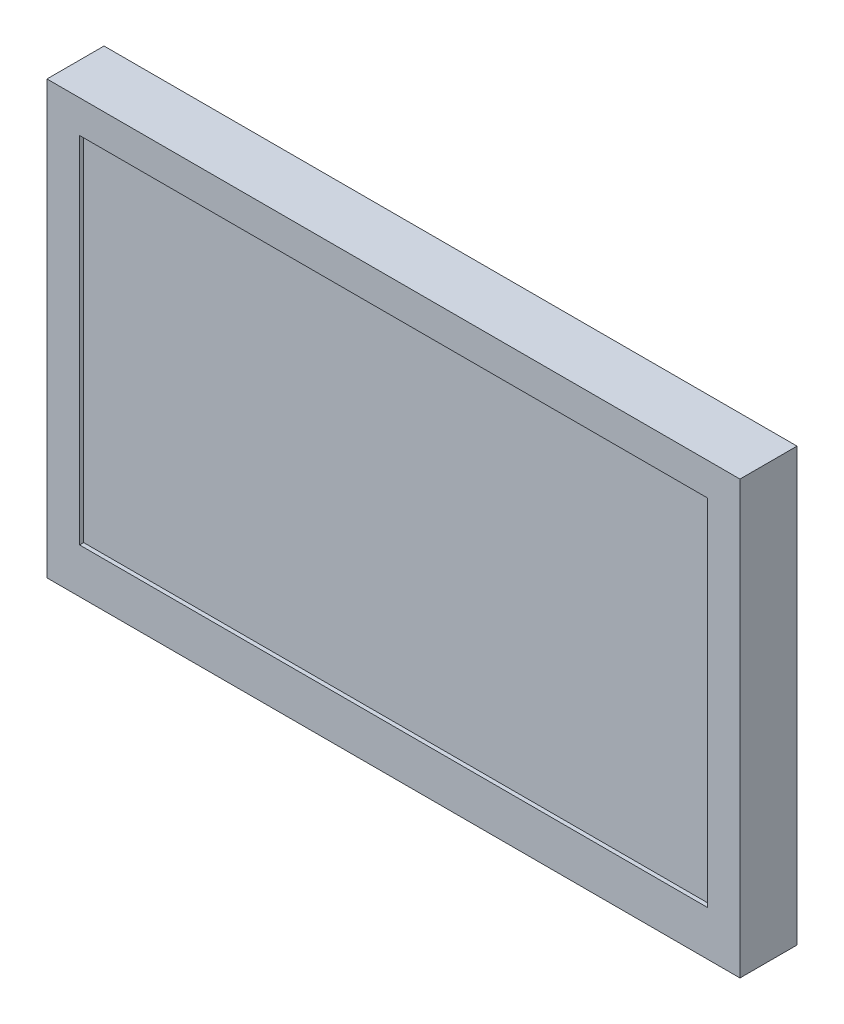
SolidWorks part; units mm, degrees
ref_plane "前视基准面" through (0, 0, 0) normal (0, 0, 1) x (1, 0, 0)
ref_plane "上视基准面" through (0, 0, 0) normal (0, 1, 0) x (1, 0, 0)
ref_plane "右视基准面" through (0, 0, 0) normal (1, 0, 0) x (0, 0, -1)
sketch "草图1" plane through (0, 0, 0) normal (0, 0, 1) x (1, 0, 0)
  line L1 (-85, -53) -> (85, -53)
  line L2 (-85, -53) -> (-85, 53)
  line L3 (-85, 53) -> (85, 53)
  line L4 (85, -53) -> (85, 53)
  line L5 (-85, -53) -> (85, 53) construction
  line L6 (-85, 53) -> (85, -53) construction
  point P0 (0, 0)
  dimension "D1" = 106
  dimension "D2" = 170
extrude "凸台-拉伸1" add sketch "草图1" against normal blind 14
sketch "草图2" plane through (0, 0, -14) normal (0, 0, -1) x (-1, 0, 0)
  circle A0 centre (37.5, 37.5) radius 2
  circle A1 centre (-37.5, 37.5) radius 2
  circle A2 centre (-37.5, -37.5) radius 2
  circle A3 centre (37.5, -37.5) radius 2
  dimension "D1" = 4
  dimension "D2" = 37.5
  dimension "D3" = 37.5
  dimension "D4" = 2
  dimension "D5" = 2
extrude "切除-拉伸1" cut sketch "草图2" against normal blind 5
sketch "草图3" plane through (0, 0, 0) normal (0, 0, 1) x (1, 0, 0)
  line L0 (-85, -53) -> (85, -53) construction
  line L1 (-77, -42) -> (77, -42)
  line L2 (-77, -42) -> (-77, 45)
  line L3 (-77, 45) -> (77, 45)
  line L4 (77, -42) -> (77, 45)
  line L5 (-77, -42) -> (77, 45) construction
  line L6 (-77, 45) -> (77, -42) construction
  line L7 (-85, 53) -> (-85, -53) construction
  point P0 (0, 1.5)
  dimension "D1" = 154
  dimension "D2" = 87
  dimension "D3" = 11
  dimension "D4" = 8
extrude "切除-拉伸2" cut sketch "草图3" against normal blind 1
